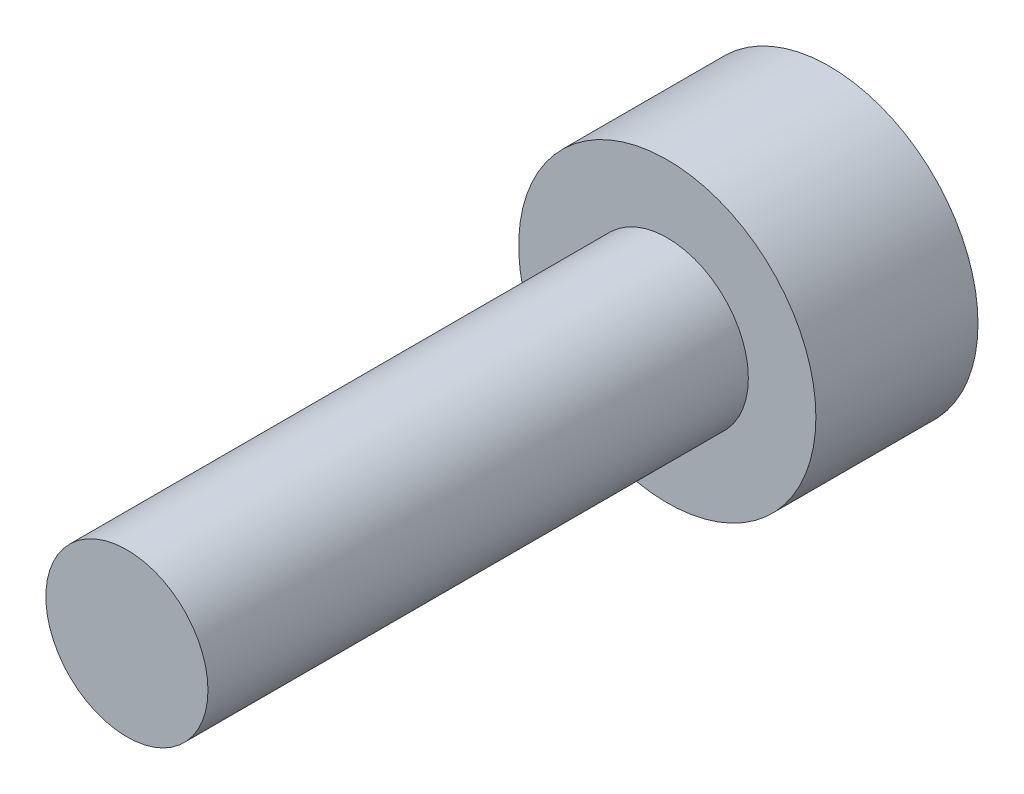
SolidWorks part; units mm, degrees
ref_plane "正面" through (0, 0, 0) normal (0, 0, 1) x (1, 0, 0)
ref_plane "平面" through (0, 0, 0) normal (0, 1, 0) x (1, 0, 0)
ref_plane "右側面" through (0, 0, 0) normal (1, 0, 0) x (0, 0, -1)
sketch "ｽｹｯﾁ1" plane through (0, 0, 0) normal (0, 0, 1) x (1, 0, 0)
  circle A0 centre (0, 0) radius 2.75
  dimension "D1" = 5.5
extrude "ﾎﾞｽ - 押し出し1" add sketch "ｽｹｯﾁ1" along normal blind 3
sketch "ｽｹｯﾁ2" plane through (0, 0, 3) normal (0, 0, 1) x (1, 0, 0)
  circle A0 centre (0, 0) radius 1.5
  dimension "D1" = 3
extrude "ﾎﾞｽ - 押し出し2" add sketch "ｽｹｯﾁ2" along normal blind 10
cosmetic thread "ねじ山1"
sketch "ｽｹｯﾁ3" plane through (0, 0, 0) normal (0, 0, -1) x (-1, 0, 0)
  line L1 (1.6636, -0.3991) -> (1.1774, 1.2412)
  line L2 (1.1774, 1.2412) -> (-0.4862, 1.6403)
  line L3 (-0.4862, 1.6403) -> (-1.6636, 0.3991)
  line L4 (-1.6636, 0.3991) -> (-1.1774, -1.2412)
  line L5 (-1.1774, -1.2412) -> (0.4862, -1.6403)
  line L6 (0.4862, -1.6403) -> (1.6636, -0.3991)
  circle A0 centre (0, 0) radius 1.4816 construction
extrude "ｶｯﾄ - 押し出し1" cut sketch "ｽｹｯﾁ3" against normal blind 2
